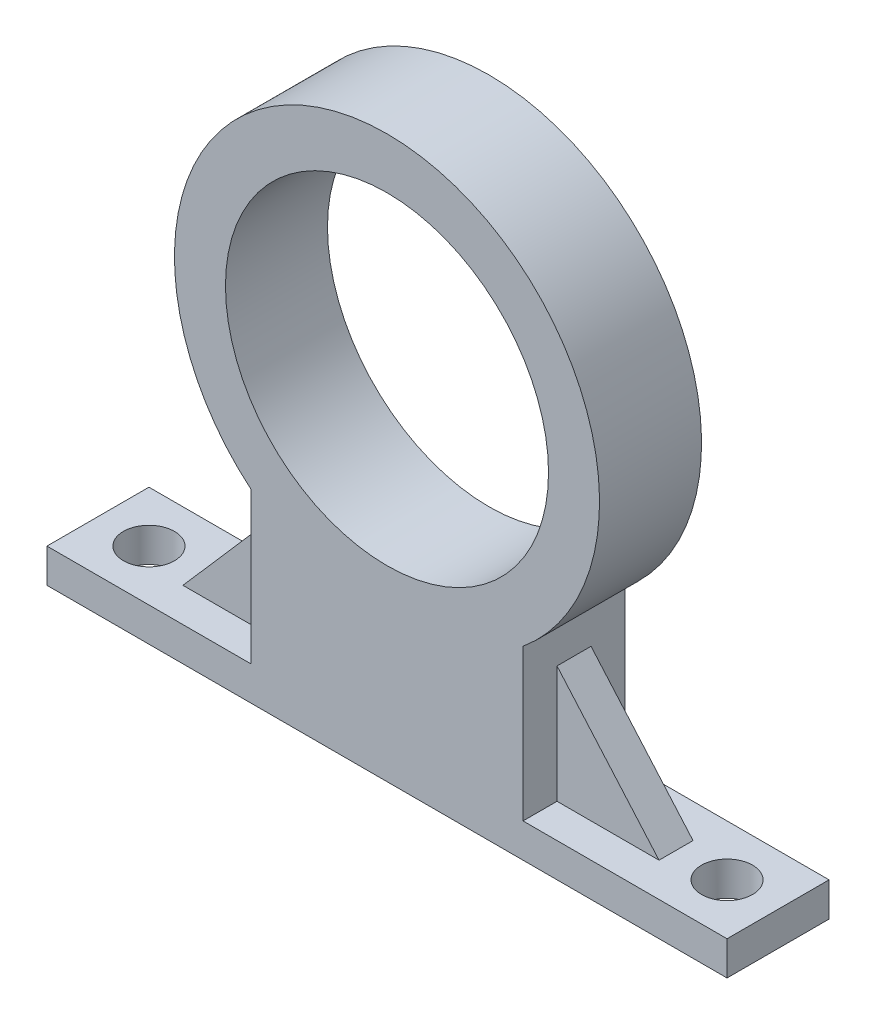
SolidWorks part; units mm, degrees
ref_plane "Front Plane" through (0, 0, 0) normal (0, 0, 1) x (1, 0, 0)
ref_plane "Top Plane" through (0, 0, 0) normal (0, 1, 0) x (1, 0, 0)
ref_plane "Right Plane" through (0, 0, 0) normal (1, 0, 0) x (0, 0, -1)
sketch "Sketch1" plane through (0, 0, 0) normal (0, 0, 1) x (1, 0, 0)
  circle A0 centre (0, 0) radius 9.5
  circle A1 centre (0, 0) radius 12.5
  dimension "D1" = 19
  dimension "D2" = 25
extrude "Boss-Extrude1" add sketch "Sketch1" along normal blind 6
ref_plane "Plane1" through (0, -12.5, 0) normal (0, -1, 0) x (-1, 0, 0)
sketch "Sketch2" plane through (0, -12.5, 0) normal (0, -1, 0) x (-1, 0, 0)
  line L0 (0, -6) -> (0, 0) construction
  line L1 (-12.5, -6) -> (12.5, -6) construction
  line L2 (12.5, -3) -> (-12.5, -3) construction
  line L3 (12.5, -6) -> (12.5, 0) construction
  line L4 (-12.5, 0) -> (-12.5, -6) construction
  line L6 (8, 0) -> (-8, 0)
  line L7 (8, 0) -> (8, -6)
  line L8 (8, -6) -> (-8, -6)
  line L9 (-8, 0) -> (-8, -6)
  line L10 (8, 0) -> (-8, -6) construction
  line L11 (8, -6) -> (-8, 0) construction
  point P11 (0, -3)
  point P18 (0, 0)
  dimension "D1" = 6
  dimension "D2" = 16
extrude "Boss-Extrude2" add sketch "Sketch2" along normal blind 8 and the other way up to next
sketch "Sketch3" plane through (8, 0, 0) normal (1, 0, 0) x (0, 0, -1)
  line L0 (0, -20.5) -> (0, -9.6047) construction
  line L1 (-6, -20.5) -> (0, -20.5)
  line L2 (-6, -20.5) -> (-6, -18.5)
  line L3 (-6, -18.5) -> (0, -18.5)
  line L4 (0, -20.5) -> (0, -18.5)
  dimension "D1" = 2
extrude "Boss-Extrude3" add sketch "Sketch3" along normal blind 12
mirror "Mirror1" about plane through (0, 0, 0) normal (1, 0, 0) of "Boss-Extrude3"
ref_plane "Plane2" through (0, 0, 3) normal (0, 0, 1) x (1, 0, 0)
sketch "Sketch6" plane through (0, 0, 3) normal (0, 0, 1) x (1, 0, 0)
  line L0 (14, -18.5) -> (8, -11.6047)
  line L1 (20, -18.5) -> (8, -18.5) construction
  line L2 (8, -18.5) -> (8, -9.6047) construction
  line L3 (8, -11.6047) -> (8, -18.5)
  line L4 (8, -18.5) -> (14, -18.5)
  dimension "D1" = 2
extrude "Boss-Extrude4" add sketch "Sketch6" along normal blind 1 and the other way blind 1
mirror "Mirror2" about plane through (0, 0, 0) normal (1, 0, 0) of "Boss-Extrude4"
sketch "Sketch7" plane through (0, -18.5, 0) normal (0, 1, 0) x (1, 0, 0)
  line L0 (-18.15, -3) -> (18.15, -3) construction
  line L1 (-14, -2) -> (-14, -4) construction
  line L2 (0, -3.3) -> (0, 3.3) construction
  circle A0 centre (-17, -3) radius 1.5
  circle A1 centre (17, -3) radius 1.5
  dimension "D1" = 3
  dimension "D2" = 3
extrude "Cut-Extrude1" cut sketch "Sketch7" against normal up to next
